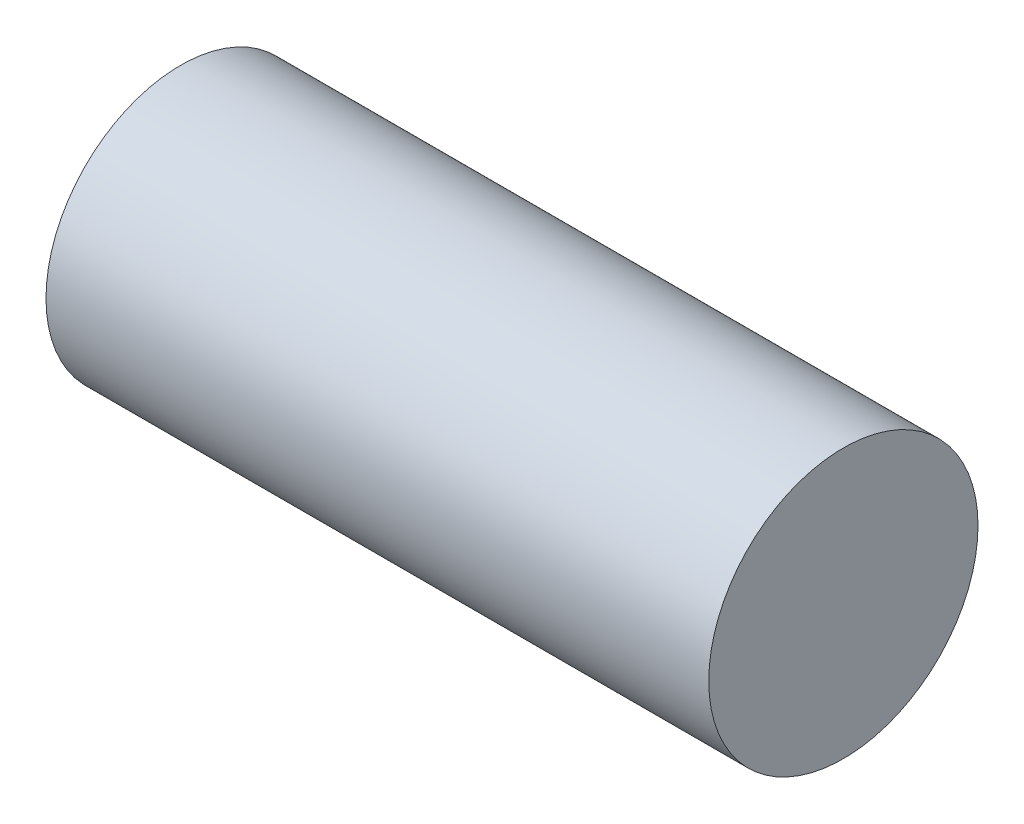
SolidWorks part; units mm, degrees
ref_plane "Front Plane" through (0, 0, 0) normal (0, 0, 1) x (1, 0, 0)
ref_plane "Top Plane" through (0, 0, 0) normal (0, 1, 0) x (1, 0, 0)
ref_plane "Right Plane" through (0, 0, 0) normal (1, 0, 0) x (0, 0, -1)
sketch "Sketch2" plane through (0, 0, 0) normal (0, 0, 1) x (1, 0, 0)
  line L0 (0, 0.0896) -> (0, 1.625)
  line L1 (0, 1.625) -> (8, 1.625)
  line L2 (8, 1.625) -> (8, 0)
  line L3 (8, 0) -> (0, 0)
  line L4 (0, 0) -> (0, 0.0896)
  dimension "D1" = 1.625
  dimension "D2" = 8
revolve "Revolve1" add sketch "Sketch2" angle 360 about L1
